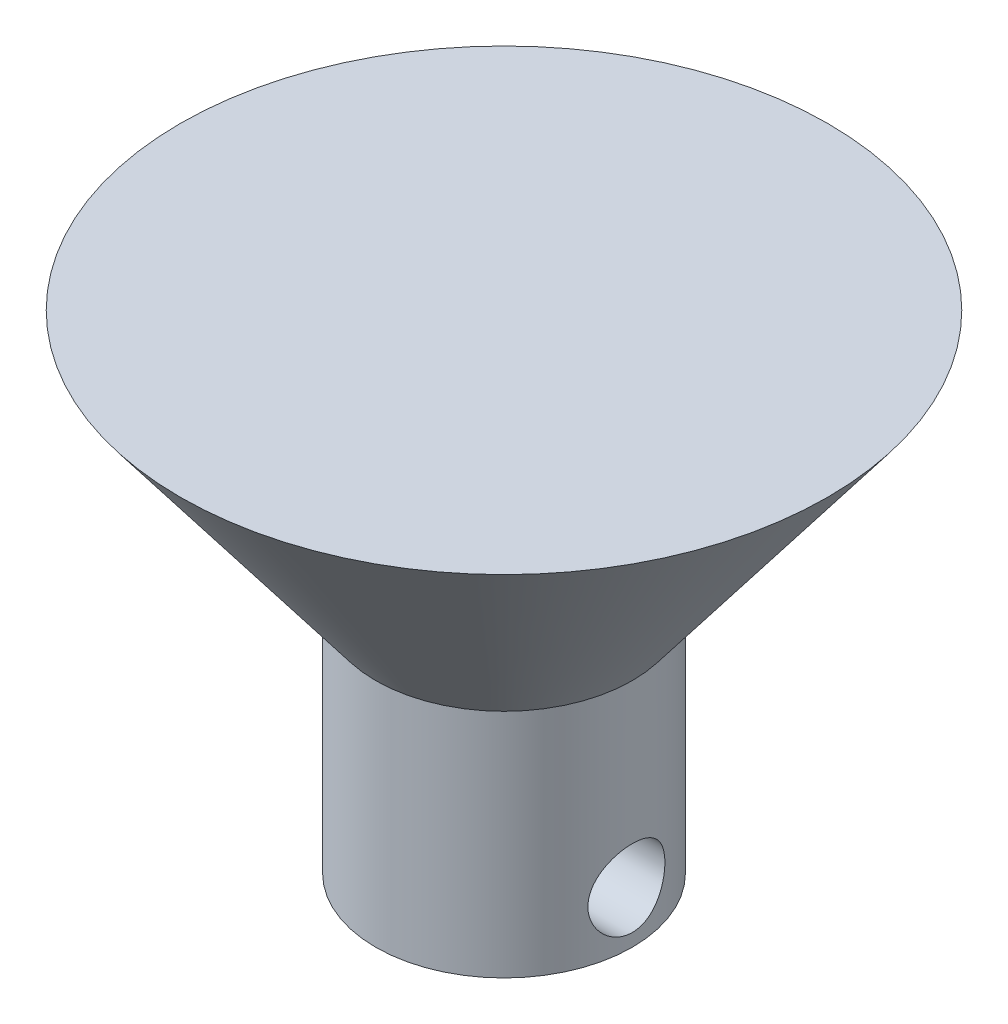
SolidWorks part; units mm, degrees
ref_plane "Front Plane" through (0, 0, 0) normal (0, 0, 1) x (1, 0, 0)
ref_plane "Top Plane" through (0, 0, 0) normal (0, 1, 0) x (1, 0, 0)
ref_plane "Right Plane" through (0, 0, 0) normal (1, 0, 0) x (0, 0, -1)
sketch "Sketch1" plane through (0, 0, 0) normal (0, 1, 0) x (1, 0, 0)
  circle A0 centre (0, 0) radius 5
  dimension "D1" = 10
extrude "body" add sketch "Sketch1" along normal blind 9
sketch "Sketch2" plane through (0, 0, 0) normal (1, 0, 0) x (0, 0, -1)
  circle A0 centre (0, 2) radius 1.5
  dimension "D1" = 2
  dimension "D2" = 3
extrude "pin insert" cut sketch "Sketch2" against normal through all and the other way through all
ref_plane "contact plane" through (0, 19, 0) normal (0, 1, 0) x (1, 0, 0)
sketch "head SA" plane through (0, 19, 0) normal (0, 1, 0) x (1, 0, 0)
  circle A0 centre (0, 0) radius 12.616
  dimension "D1" = 25.232
loft "cone" add profiles "head SA" section "head SA" section face at (0, 9, 5)
